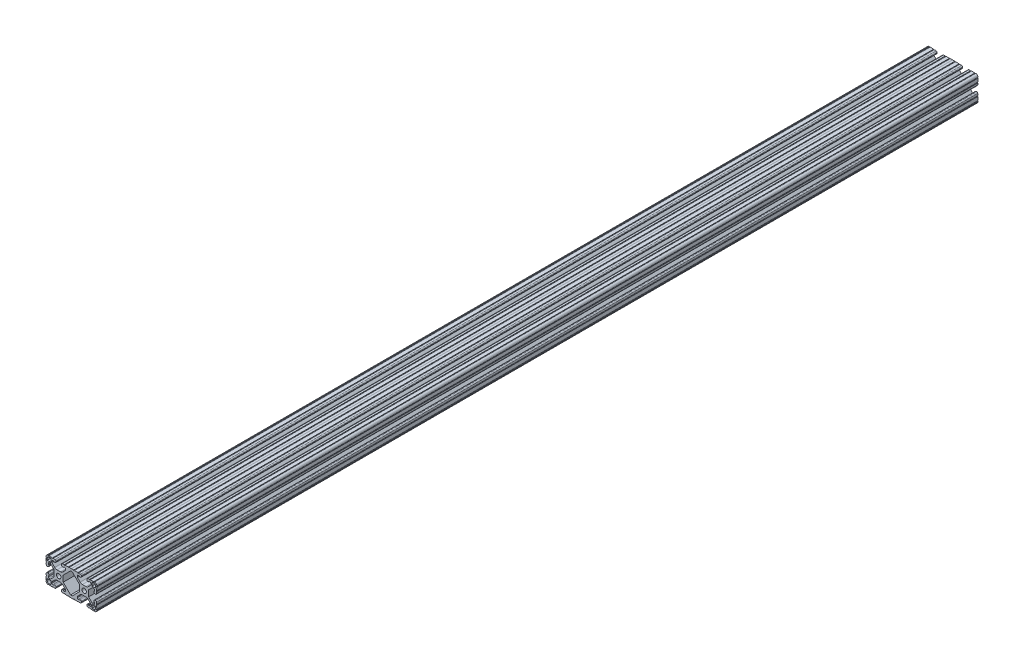
SolidWorks part; units mm, degrees
ref_plane "Front Plane" through (0, 0, 0) normal (0, 0, 1) x (1, 0, 0)
ref_plane "Top Plane" through (0, 0, 0) normal (0, 1, 0) x (1, 0, 0)
ref_plane "Right Plane" through (0, 0, 0) normal (1, 0, 0) x (0, 0, -1)
sketch "Sketch1" plane through (0, 0, 0) normal (0, 0, 1) x (1, 0, 0)
  line L0 (0, 19.05) -> (-19.1669, 19.05) construction
  line L1 (-6.7564, 0) -> (-6.7564, 4.6011)
  line L2 (-8.7357, 18.8026) -> (-15.7642, 19.0481) construction
  line L3 (-17.655, 18.5041) -> (-4.0303, 18.0283) construction
  line L4 (-5.5829, 18.6925) -> (-5.7212, 14.7325) construction
  line L5 (-11.8364, 17.2212) -> (-11.8364, 11.8364)
  line L6 (-2.6337, 6.7564) -> (0, 6.7564)
  line L7 (0, 0) -> (0, 19.05) construction
  line L8 (0, 0) -> (-19.1669, 0) construction
  line L9 (1.0776, 1.0776) -> (-1.0776, -1.0776) construction
  line L10 (-5.9923, 8.1476) -> (-9.915, 12.0703)
  line L11 (-6.7564, 4.6011) -> (-12.4423, 10.287)
  line L12 (-11.8364, 11.8364) -> (-17.2212, 11.8364)
  line L13 (0, 0) -> (-19.1669, 19.1669) construction
  line L14 (-15.7642, 19.0481) -> (-5.5829, 18.6925)
  line L15 (-4.064, 17.0637) -> (-4.0924, 16.2514)
  line L17 (-19.0481, 15.7642) -> (-18.6925, 5.5829)
  line L19 (-17.2212, 11.8364) -> (-17.2212, 14.4272)
  line L20 (-11.8364, 17.2212) -> (-14.4272, 17.2212)
  line L21 (-10.287, 12.9683) -> (-10.287, 14.3745)
  line L22 (-14.3745, 10.287) -> (-12.4423, 10.287)
  line L23 (-9.017, 15.6445) -> (-6.8707, 15.6445)
  line L24 (-6.8707, 15.6445) -> (-6.8707, 14.7325)
  line L25 (-5.7212, 14.7325) -> (-6.8707, 14.7325)
  line L26 (-17.0637, 4.064) -> (-16.2514, 4.0924)
  line L27 (-14.7325, 5.7212) -> (-14.7325, 6.8707)
  line L28 (-15.6445, 6.8707) -> (-14.7325, 6.8707)
  line L29 (-15.6445, 9.017) -> (-15.6445, 6.8707)
  circle A0 centre (0, 0) radius 3.3274
  arc A5 (-15.7642, 19.0481) -> (-19.0481, 15.7642) centre (-15.875, 15.875) ccw
  arc A7 (-9.3449, 18.8239) -> (-8.1264, 18.7813) centre (-8.7357, 18.8026) ccw
  arc A10 (-17.2212, 14.4272) -> (-14.4272, 17.2212) centre (-14.4272, 14.4272) cw
  arc A11 (-4.0924, 16.2514) -> (-5.7212, 14.7325) centre (-5.6662, 16.3064) cw
  arc A12 (-5.5829, 18.6925) -> (-4.064, 17.0637) centre (-5.6378, 17.1187) cw
  arc A13 (-5.9923, 8.1476) -> (-2.6337, 6.7564) centre (-2.6337, 11.5062) ccw
  arc A14 (-9.915, 12.0703) -> (-10.287, 12.9683) centre (-9.017, 12.9683) cw
  arc A15 (-10.287, 14.3745) -> (-9.017, 15.6445) centre (-9.017, 14.3745) cw
  arc A16 (-15.6949, 19.0456) -> (-14.4764, 19.0031) centre (-15.0857, 19.0244) ccw
  arc A17 (-18.6925, 5.5829) -> (-17.0637, 4.064) centre (-17.1187, 5.6378) ccw
  arc A18 (-16.2514, 4.0924) -> (-14.7325, 5.7212) centre (-16.3064, 5.6662) ccw
  arc A19 (-14.3745, 10.287) -> (-15.6445, 9.017) centre (-14.3745, 9.017) ccw
  arc A20 (-18.8239, 9.3449) -> (-18.7813, 8.1264) centre (-18.8026, 8.7357) cw
  arc A21 (-19.0456, 15.6949) -> (-19.0031, 14.4764) centre (-19.0244, 15.0857) cw
  point P27 (-5.7298, 13.1063)
  point P49 (-4.009, 18.6376)
  point P55 (-10.287, 12.4423)
  dimension "D1" = 6.6548
  dimension "D5" = 20.574
  dimension "D9" = 2
  dimension "D2" = 38.1
  dimension "D12" = 0.6096
  dimension "D10" = 3.175
  dimension "D13" = 2.794
  dimension "D14" = 7.2136
  dimension "D7" = 1.5748
  dimension "D20" = 4.7498
  dimension "D21" = 1.27
  dimension "D3" = 13.5128
  dimension "D4" = 13.5128
  dimension "D6" = 38.1
  dimension "D8" = 3.048
  dimension "D11" = 19.05
  dimension "D15" = 5.3848
  dimension "D16" = 3.9624
  dimension "D17" = 3.048
  dimension "D18" = 8.128
  dimension "D19" = 13.7414
  dimension "D22" = 10.3124
  dimension "D23" = 3.9624
sketch "Sketch3" plane through (0, 0, 0) normal (0, 0, 1) x (1, 0, 0)
  line L0 (0, 0) -> (19.05, 0) construction
  line L1 (19.05, 19.1628) -> (19.05, 15.6445) construction
  line L2 (15.7642, 19.0481) -> (19.05, 19.1628)
  line L3 (17.7998, 15.6445) -> (20.3002, 15.6445)
  line L4 (17.7998, -15.6445) -> (20.3002, -15.6445)
  line L5 (19.05, -15.6445) -> (19.05, -19.1628) construction
  line L6 (15.7642, -19.0481) -> (19.05, -19.1628)
  line L7 (40.7337, -6.7564) -> (35.4663, -6.7564)
  line L8 (-2.6337, 6.7564) -> (0, 6.7564) construction
  line L9 (-5.9923, 8.1476) -> (-9.915, 12.0703) construction
  line L10 (-10.287, 12.9683) -> (-10.287, 14.3745) construction
  line L11 (-9.017, 15.6445) -> (-6.8707, 15.6445) construction
  line L12 (-6.8707, 15.6445) -> (-6.8707, 14.7325) construction
  line L13 (-5.7212, 14.7325) -> (-6.8707, 14.7325) construction
  line L14 (-4.064, 17.0637) -> (-4.0924, 16.2514) construction
  line L15 (-15.7642, 19.0481) -> (-5.5829, 18.6925) construction
  line L16 (-19.0481, 15.7642) -> (-18.6925, 5.5829) construction
  line L17 (-17.0637, 4.064) -> (-16.2514, 4.0924) construction
  line L18 (-14.7325, 5.7212) -> (-14.7325, 6.8707) construction
  line L19 (-15.6445, 6.8707) -> (-14.7325, 6.8707) construction
  line L20 (-15.6445, 9.017) -> (-15.6445, 6.8707) construction
  line L21 (-14.3745, 10.287) -> (-12.4423, 10.287) construction
  line L22 (-6.7564, 4.6011) -> (-12.4423, 10.287) construction
  line L23 (-6.7564, 0) -> (-6.7564, 4.6011) construction
  line L24 (-2.6337, 6.7564) -> (2.6337, 6.7564)
  line L25 (-5.9923, 8.1476) -> (-9.915, 12.0703)
  line L26 (-10.287, 12.9683) -> (-10.287, 14.3745)
  line L27 (-9.017, 15.6445) -> (-6.8707, 15.6445)
  line L28 (-6.8707, 15.6445) -> (-6.8707, 14.7325)
  line L29 (-5.7212, 14.7325) -> (-6.8707, 14.7325)
  line L30 (-4.064, 17.0637) -> (-4.0924, 16.2514)
  line L31 (-15.7642, 19.0481) -> (-15.6949, 19.0456)
  line L32 (-19.0481, 15.7642) -> (-19.0456, 15.6949)
  line L33 (-17.0637, 4.064) -> (-16.2514, 4.0924)
  line L34 (-14.7325, 5.7212) -> (-14.7325, 6.8707)
  line L35 (-15.6445, 6.8707) -> (-14.7325, 6.8707)
  line L36 (-15.6445, 9.017) -> (-15.6445, 6.8707)
  line L37 (-14.3745, 10.287) -> (-12.4423, 10.287)
  line L38 (-6.7564, 4.6011) -> (-12.4423, 10.287)
  line L39 (-6.7564, -4.6011) -> (-6.7564, 4.6011)
  line L40 (0, 0) -> (-6.7564, 0) construction
  line L41 (0, 0) -> (0, 6.7564) construction
  line L42 (-8.1264, 18.7813) -> (-5.5829, 18.6925)
  line L43 (-14.4764, 19.0031) -> (-9.3449, 18.8239)
  line L44 (-11.8364, 11.8364) -> (-11.8364, 17.2212)
  line L45 (-17.2212, 11.8364) -> (-11.8364, 11.8364)
  line L46 (-17.2212, 14.4272) -> (-17.2212, 11.8364)
  line L47 (-11.8364, 17.2212) -> (-14.4272, 17.2212)
  line L48 (-11.8364, 11.8364) -> (-11.8364, 17.2212)
  line L49 (-17.2212, 11.8364) -> (-11.8364, 11.8364)
  line L50 (-17.2212, 14.4272) -> (-17.2212, 11.8364)
  line L51 (-11.8364, 17.2212) -> (-14.4272, 17.2212)
  line L52 (-19.0031, 14.4764) -> (-18.8239, 9.3449)
  line L53 (-18.7813, 8.1264) -> (-18.6925, 5.5829)
  line L54 (44.0923, -8.1476) -> (48.015, -12.0703)
  line L55 (48.387, -12.9683) -> (48.387, -14.3745)
  line L56 (47.117, -15.6445) -> (44.9707, -15.6445)
  line L57 (44.9707, -15.6445) -> (44.9707, -14.7325)
  line L58 (43.8212, -14.7325) -> (44.9707, -14.7325)
  line L59 (42.164, -17.0637) -> (42.1924, -16.2514)
  line L60 (14.4764, 19.0031) -> (9.3449, 18.8239)
  line L61 (8.1264, 18.7813) -> (5.5829, 18.6925)
  line L62 (6.7564, -4.6011) -> (6.7564, 4.6011)
  line L63 (6.7564, 4.6011) -> (17.7998, 15.6445)
  line L64 (53.8642, -19.0481) -> (53.7949, -19.0456)
  line L65 (57.1481, -15.7642) -> (57.1456, -15.6949)
  line L66 (55.1637, -4.064) -> (54.3514, -4.0924)
  line L67 (52.8325, -5.7212) -> (52.8325, -6.8707)
  line L68 (53.7445, -6.8707) -> (52.8325, -6.8707)
  line L69 (53.7445, -9.017) -> (53.7445, -6.8707)
  line L70 (15.7642, 19.0481) -> (15.6949, 19.0456)
  line L71 (4.064, 17.0637) -> (4.0924, 16.2514)
  line L72 (5.7212, 14.7325) -> (6.8707, 14.7325)
  line L73 (6.8707, 15.6445) -> (6.8707, 14.7325)
  line L74 (9.017, 15.6445) -> (6.8707, 15.6445)
  line L75 (10.287, 12.9683) -> (10.287, 14.3745)
  line L76 (5.9923, 8.1476) -> (9.915, 12.0703)
  line L77 (5.9923, -8.1476) -> (9.915, -12.0703)
  line L78 (10.287, -12.9683) -> (10.287, -14.3745)
  line L79 (9.017, -15.6445) -> (6.8707, -15.6445)
  line L80 (6.8707, -15.6445) -> (6.8707, -14.7325)
  line L81 (5.7212, -14.7325) -> (6.8707, -14.7325)
  line L82 (4.064, -17.0637) -> (4.0924, -16.2514)
  line L83 (15.7642, -19.0481) -> (15.6949, -19.0456)
  line L84 (52.4745, -10.287) -> (50.5423, -10.287)
  line L85 (44.8564, -4.6011) -> (50.5423, -10.287)
  line L86 (46.2264, -18.7813) -> (43.6829, -18.6925)
  line L87 (52.5764, -19.0031) -> (47.4449, -18.8239)
  line L88 (49.9364, -11.8364) -> (49.9364, -17.2212)
  line L89 (55.3212, -11.8364) -> (49.9364, -11.8364)
  line L90 (6.7564, -4.6011) -> (17.7998, -15.6445)
  line L91 (8.1264, -18.7813) -> (5.5829, -18.6925)
  line L92 (14.4764, -19.0031) -> (9.3449, -18.8239)
  line L93 (55.3212, -14.4272) -> (55.3212, -11.8364)
  line L94 (49.9364, -17.2212) -> (52.5272, -17.2212)
  line L95 (57.1031, -14.4764) -> (56.9239, -9.3449)
  line L96 (56.8813, -8.1264) -> (56.7925, -5.5829)
  line L97 (23.6236, -19.0031) -> (28.7551, -18.8239)
  line L98 (29.9736, -18.7813) -> (32.5171, -18.6925)
  line L99 (-18.7813, -8.1264) -> (-18.6925, -5.5829)
  line L100 (-19.0031, -14.4764) -> (-18.8239, -9.3449)
  line L101 (-11.8364, -17.2212) -> (-14.4272, -17.2212)
  line L102 (-17.2212, -14.4272) -> (-17.2212, -11.8364)
  line L103 (-17.2212, -11.8364) -> (-11.8364, -11.8364)
  line L104 (-11.8364, -11.8364) -> (-11.8364, -17.2212)
  line L105 (-14.4764, -19.0031) -> (-9.3449, -18.8239)
  line L106 (-8.1264, -18.7813) -> (-5.5829, -18.6925)
  line L107 (-6.7564, -4.6011) -> (-12.4423, -10.287)
  line L108 (-14.3745, -10.287) -> (-12.4423, -10.287)
  line L109 (-15.6445, -9.017) -> (-15.6445, -6.8707)
  line L110 (-15.6445, -6.8707) -> (-14.7325, -6.8707)
  line L111 (-14.7325, -5.7212) -> (-14.7325, -6.8707)
  line L112 (-17.0637, -4.064) -> (-16.2514, -4.0924)
  line L113 (-19.0481, -15.7642) -> (-19.0456, -15.6949)
  line L114 (-15.7642, -19.0481) -> (-15.6949, -19.0456)
  line L115 (-4.064, -17.0637) -> (-4.0924, -16.2514)
  line L116 (-5.7212, -14.7325) -> (-6.8707, -14.7325)
  line L117 (-6.8707, -15.6445) -> (-6.8707, -14.7325)
  line L118 (-9.017, -15.6445) -> (-6.8707, -15.6445)
  line L119 (-10.287, -12.9683) -> (-10.287, -14.3745)
  line L120 (-5.9923, -8.1476) -> (-9.915, -12.0703)
  line L121 (-2.6337, -6.7564) -> (2.6337, -6.7564)
  line L122 (31.3436, -4.6011) -> (20.3002, -15.6445)
  line L123 (22.3358, -19.0481) -> (22.4051, -19.0456)
  line L124 (34.036, -17.0637) -> (34.0076, -16.2514)
  line L125 (32.3788, -14.7325) -> (31.2293, -14.7325)
  line L126 (31.2293, -15.6445) -> (31.2293, -14.7325)
  line L127 (29.083, -15.6445) -> (31.2293, -15.6445)
  line L128 (27.813, -12.9683) -> (27.813, -14.3745)
  line L129 (32.1077, -8.1476) -> (28.185, -12.0703)
  line L130 (32.1077, 8.1476) -> (28.185, 12.0703)
  line L131 (27.813, 12.9683) -> (27.813, 14.3745)
  line L132 (29.083, 15.6445) -> (31.2293, 15.6445)
  line L133 (31.2293, 15.6445) -> (31.2293, 14.7325)
  line L134 (32.3788, 14.7325) -> (31.2293, 14.7325)
  line L135 (34.036, 17.0637) -> (34.0076, 16.2514)
  line L136 (22.3358, 19.0481) -> (22.4051, 19.0456)
  line L137 (31.3436, 4.6011) -> (20.3002, 15.6445)
  line L138 (31.3436, -4.6011) -> (31.3436, 4.6011)
  line L139 (29.9736, 18.7813) -> (32.5171, 18.6925)
  line L140 (23.6236, 19.0031) -> (28.7551, 18.8239)
  line L141 (56.8813, 8.1264) -> (56.7925, 5.5829)
  line L142 (57.1031, 14.4764) -> (56.9239, 9.3449)
  line L143 (49.9364, 17.2212) -> (52.5272, 17.2212)
  line L144 (55.3212, 14.4272) -> (55.3212, 11.8364)
  line L145 (55.3212, 11.8364) -> (49.9364, 11.8364)
  line L146 (49.9364, 11.8364) -> (49.9364, 17.2212)
  line L147 (52.5764, 19.0031) -> (47.4449, 18.8239)
  line L148 (46.2264, 18.7813) -> (43.6829, 18.6925)
  line L149 (44.8564, -4.6011) -> (44.8564, 4.6011)
  line L150 (44.8564, 4.6011) -> (50.5423, 10.287)
  line L151 (52.4745, 10.287) -> (50.5423, 10.287)
  line L152 (53.7445, 9.017) -> (53.7445, 6.8707)
  line L153 (53.7445, 6.8707) -> (52.8325, 6.8707)
  line L154 (52.8325, 5.7212) -> (52.8325, 6.8707)
  line L155 (55.1637, 4.064) -> (54.3514, 4.0924)
  line L156 (57.1481, 15.7642) -> (57.1456, 15.6949)
  line L157 (53.8642, 19.0481) -> (53.7949, 19.0456)
  line L158 (42.164, 17.0637) -> (42.1924, 16.2514)
  line L159 (43.8212, 14.7325) -> (44.9707, 14.7325)
  line L160 (44.9707, 15.6445) -> (44.9707, 14.7325)
  line L161 (47.117, 15.6445) -> (44.9707, 15.6445)
  line L162 (48.387, 12.9683) -> (48.387, 14.3745)
  line L163 (44.0923, 8.1476) -> (48.015, 12.0703)
  line L164 (40.7337, 6.7564) -> (35.4663, 6.7564)
  line L165 (22.3358, -19.0481) -> (19.05, -19.1628)
  line L166 (22.3358, 19.0481) -> (19.05, 19.1628)
  arc A0 (53.7949, -19.0456) -> (52.5764, -19.0031) centre (53.1857, -19.0244) ccw
  arc A1 (44.0923, -8.1476) -> (40.7337, -6.7564) centre (40.7337, -11.5062) ccw
  arc A2 (48.387, -12.9683) -> (48.015, -12.0703) centre (47.117, -12.9683) ccw
  arc A3 (47.117, -15.6445) -> (48.387, -14.3745) centre (47.117, -14.3745) ccw
  arc A4 (43.8212, -14.7325) -> (42.1924, -16.2514) centre (43.7662, -16.3064) ccw
  arc A5 (42.164, -17.0637) -> (43.6829, -18.6925) centre (43.7378, -17.1187) ccw
  arc A6 (53.8642, -19.0481) -> (57.1481, -15.7642) centre (53.975, -15.875) ccw
  arc A7 (56.7925, -5.5829) -> (55.1637, -4.064) centre (55.2187, -5.6378) ccw
  arc A8 (54.3514, -4.0924) -> (52.8325, -5.7212) centre (54.4064, -5.6662) ccw
  arc A9 (-15.6949, 19.0456) -> (-14.4764, 19.0031) centre (-15.0857, 19.0244) ccw construction
  arc A10 (-5.9923, 8.1476) -> (-2.6337, 6.7564) centre (-2.6337, 11.5062) ccw construction
  arc A11 (-10.287, 12.9683) -> (-9.915, 12.0703) centre (-9.017, 12.9683) ccw construction
  arc A12 (-9.017, 15.6445) -> (-10.287, 14.3745) centre (-9.017, 14.3745) ccw construction
  arc A13 (-5.7212, 14.7325) -> (-4.0924, 16.2514) centre (-5.6662, 16.3064) ccw construction
  arc A14 (-4.064, 17.0637) -> (-5.5829, 18.6925) centre (-5.6378, 17.1187) ccw construction
  arc A15 (-15.7642, 19.0481) -> (-19.0481, 15.7642) centre (-15.875, 15.875) ccw construction
  arc A16 (-18.6925, 5.5829) -> (-17.0637, 4.064) centre (-17.1187, 5.6378) ccw construction
  arc A17 (-16.2514, 4.0924) -> (-14.7325, 5.7212) centre (-16.3064, 5.6662) ccw construction
  arc A18 (-14.3745, 10.287) -> (-15.6445, 9.017) centre (-14.3745, 9.017) ccw construction
  arc A19 (-9.3449, 18.8239) -> (-8.1264, 18.7813) centre (-8.7357, 18.8026) ccw construction
  arc A20 (-18.7813, 8.1264) -> (-18.8239, 9.3449) centre (-18.8026, 8.7357) ccw construction
  arc A21 (-19.0031, 14.4764) -> (-19.0456, 15.6949) centre (-19.0244, 15.0857) ccw construction
  arc A22 (-15.6949, 19.0456) -> (-14.4764, 19.0031) centre (-15.0857, 19.0244) ccw
  arc A23 (-5.9923, 8.1476) -> (-2.6337, 6.7564) centre (-2.6337, 11.5062) ccw
  arc A24 (-10.287, 12.9683) -> (-9.915, 12.0703) centre (-9.017, 12.9683) ccw
  arc A25 (-9.017, 15.6445) -> (-10.287, 14.3745) centre (-9.017, 14.3745) ccw
  arc A26 (-5.7212, 14.7325) -> (-4.0924, 16.2514) centre (-5.6662, 16.3064) ccw
  arc A27 (-4.064, 17.0637) -> (-5.5829, 18.6925) centre (-5.6378, 17.1187) ccw
  arc A28 (-15.7642, 19.0481) -> (-19.0481, 15.7642) centre (-15.875, 15.875) ccw
  arc A29 (-18.6925, 5.5829) -> (-17.0637, 4.064) centre (-17.1187, 5.6378) ccw
  arc A30 (-16.2514, 4.0924) -> (-14.7325, 5.7212) centre (-16.3064, 5.6662) ccw
  arc A31 (-14.3745, 10.287) -> (-15.6445, 9.017) centre (-14.3745, 9.017) ccw
  arc A32 (-9.3449, 18.8239) -> (-8.1264, 18.7813) centre (-8.7357, 18.8026) ccw
  arc A33 (-18.7813, 8.1264) -> (-18.8239, 9.3449) centre (-18.8026, 8.7357) ccw
  arc A34 (-19.0031, 14.4764) -> (-19.0456, 15.6949) centre (-19.0244, 15.0857) ccw
  arc A35 (52.4745, -10.287) -> (53.7445, -9.017) centre (52.4745, -9.017) ccw
  circle A36 centre (0, 0) radius 3.3274
  circle A37 centre (0, 0) radius 3.3274
  arc A38 (-14.4272, 17.2212) -> (-17.2212, 14.4272) centre (-14.4272, 14.4272) ccw
  arc A39 (-14.4272, 17.2212) -> (-17.2212, 14.4272) centre (-14.4272, 14.4272) ccw
  arc A40 (47.4449, -18.8239) -> (46.2264, -18.7813) centre (46.8357, -18.8026) ccw
  arc A41 (56.8813, -8.1264) -> (56.9239, -9.3449) centre (56.9026, -8.7357) ccw
  arc A42 (9.3449, 18.8239) -> (8.1264, 18.7813) centre (8.7357, 18.8026) cw
  arc A43 (57.1031, -14.4764) -> (57.1456, -15.6949) centre (57.1244, -15.0857) ccw
  arc A44 (52.5272, -17.2212) -> (55.3212, -14.4272) centre (52.5272, -14.4272) ccw
  arc A45 (28.7551, -18.8239) -> (29.9736, -18.7813) centre (29.3643, -18.8026) cw
  arc A46 (34.036, -17.0637) -> (32.5171, -18.6925) centre (32.4622, -17.1187) cw
  arc A47 (4.064, 17.0637) -> (5.5829, 18.6925) centre (5.6378, 17.1187) cw
  arc A48 (5.7212, 14.7325) -> (4.0924, 16.2514) centre (5.6662, 16.3064) cw
  arc A49 (9.017, 15.6445) -> (10.287, 14.3745) centre (9.017, 14.3745) cw
  arc A50 (10.287, 12.9683) -> (9.915, 12.0703) centre (9.017, 12.9683) cw
  arc A51 (5.9923, 8.1476) -> (2.6337, 6.7564) centre (2.6337, 11.5062) cw
  arc A52 (15.6949, 19.0456) -> (14.4764, 19.0031) centre (15.0857, 19.0244) cw
  arc A53 (32.3788, -14.7325) -> (34.0076, -16.2514) centre (32.4338, -16.3064) cw
  arc A54 (15.6949, -19.0456) -> (14.4764, -19.0031) centre (15.0857, -19.0244) ccw
  arc A55 (5.9923, -8.1476) -> (2.6337, -6.7564) centre (2.6337, -11.5062) ccw
  arc A56 (10.287, -12.9683) -> (9.915, -12.0703) centre (9.017, -12.9683) ccw
  arc A57 (9.017, -15.6445) -> (10.287, -14.3745) centre (9.017, -14.3745) ccw
  arc A58 (5.7212, -14.7325) -> (4.0924, -16.2514) centre (5.6662, -16.3064) ccw
  arc A59 (4.064, -17.0637) -> (5.5829, -18.6925) centre (5.6378, -17.1187) ccw
  arc A60 (29.083, -15.6445) -> (27.813, -14.3745) centre (29.083, -14.3745) cw
  arc A61 (27.813, -12.9683) -> (28.185, -12.0703) centre (29.083, -12.9683) cw
  arc A62 (32.1077, -8.1476) -> (35.4663, -6.7564) centre (35.4663, -11.5062) cw
  arc A63 (22.4051, -19.0456) -> (23.6236, -19.0031) centre (23.0143, -19.0244) cw
  arc A64 (9.3449, -18.8239) -> (8.1264, -18.7813) centre (8.7357, -18.8026) ccw
  arc A65 (22.4051, 19.0456) -> (23.6236, 19.0031) centre (23.0143, 19.0244) ccw
  arc A66 (32.1077, 8.1476) -> (35.4663, 6.7564) centre (35.4663, 11.5062) ccw
  arc A67 (-14.4272, -17.2212) -> (-17.2212, -14.4272) centre (-14.4272, -14.4272) cw
  arc A68 (27.813, 12.9683) -> (28.185, 12.0703) centre (29.083, 12.9683) ccw
  arc A69 (-19.0031, -14.4764) -> (-19.0456, -15.6949) centre (-19.0244, -15.0857) cw
  arc A70 (-18.7813, -8.1264) -> (-18.8239, -9.3449) centre (-18.8026, -8.7357) cw
  arc A71 (-9.3449, -18.8239) -> (-8.1264, -18.7813) centre (-8.7357, -18.8026) cw
  arc A72 (-14.3745, -10.287) -> (-15.6445, -9.017) centre (-14.3745, -9.017) cw
  arc A73 (-16.2514, -4.0924) -> (-14.7325, -5.7212) centre (-16.3064, -5.6662) cw
  arc A74 (-18.6925, -5.5829) -> (-17.0637, -4.064) centre (-17.1187, -5.6378) cw
  arc A75 (-15.7642, -19.0481) -> (-19.0481, -15.7642) centre (-15.875, -15.875) cw
  arc A76 (-4.064, -17.0637) -> (-5.5829, -18.6925) centre (-5.6378, -17.1187) cw
  arc A77 (-5.7212, -14.7325) -> (-4.0924, -16.2514) centre (-5.6662, -16.3064) cw
  arc A78 (-9.017, -15.6445) -> (-10.287, -14.3745) centre (-9.017, -14.3745) cw
  arc A79 (-10.287, -12.9683) -> (-9.915, -12.0703) centre (-9.017, -12.9683) cw
  arc A80 (-5.9923, -8.1476) -> (-2.6337, -6.7564) centre (-2.6337, -11.5062) cw
  arc A81 (-15.6949, -19.0456) -> (-14.4764, -19.0031) centre (-15.0857, -19.0244) cw
  arc A82 (29.083, 15.6445) -> (27.813, 14.3745) centre (29.083, 14.3745) ccw
  arc A83 (32.3788, 14.7325) -> (34.0076, 16.2514) centre (32.4338, 16.3064) ccw
  arc A84 (34.036, 17.0637) -> (32.5171, 18.6925) centre (32.4622, 17.1187) ccw
  arc A85 (28.7551, 18.8239) -> (29.9736, 18.7813) centre (29.3643, 18.8026) ccw
  arc A86 (52.5272, 17.2212) -> (55.3212, 14.4272) centre (52.5272, 14.4272) cw
  circle A87 centre (38.1, 0) radius 3.3274
  arc A88 (57.1031, 14.4764) -> (57.1456, 15.6949) centre (57.1244, 15.0857) cw
  arc A89 (56.8813, 8.1264) -> (56.9239, 9.3449) centre (56.9026, 8.7357) cw
  arc A90 (47.4449, 18.8239) -> (46.2264, 18.7813) centre (46.8357, 18.8026) cw
  arc A91 (52.4745, 10.287) -> (53.7445, 9.017) centre (52.4745, 9.017) cw
  arc A92 (54.3514, 4.0924) -> (52.8325, 5.7212) centre (54.4064, 5.6662) cw
  arc A93 (56.7925, 5.5829) -> (55.1637, 4.064) centre (55.2187, 5.6378) cw
  arc A94 (53.8642, 19.0481) -> (57.1481, 15.7642) centre (53.975, 15.875) cw
  arc A95 (42.164, 17.0637) -> (43.6829, 18.6925) centre (43.7378, 17.1187) cw
  arc A96 (43.8212, 14.7325) -> (42.1924, 16.2514) centre (43.7662, 16.3064) cw
  arc A97 (47.117, 15.6445) -> (48.387, 14.3745) centre (47.117, 14.3745) cw
  arc A98 (48.387, 12.9683) -> (48.015, 12.0703) centre (47.117, 12.9683) cw
  arc A99 (44.0923, 8.1476) -> (40.7337, 6.7564) centre (40.7337, 11.5062) cw
  arc A100 (53.7949, 19.0456) -> (52.5764, 19.0031) centre (53.1857, 19.0244) cw
  point P201 (6.7564, 0)
  point P293 (31.3436, 0)
  dimension "D2" = 3.048
  dimension "D3" = 19.05
  dimension "D1" = 0
extrude "Extrude1" add sketch "Sketch3" along normal mid plane 1828.8
sketch "Sketch4" plane through (0, 0, -914.4) normal (0, 0, -1) x (-1, 0, 0)
  line L1 (-58.7594, 19.6469) -> (20.3233, 19.6469)
  line L2 (-58.7594, 19.6469) -> (-58.7594, -20.0712)
  line L3 (-58.7594, -20.0712) -> (20.3233, -20.0712)
  line L4 (20.3233, 19.6469) -> (20.3233, -20.0712)
extrude "Cut-Extrude1" cut sketch "Sketch4" against normal blind 508
equation "\"D11@Sketch1\" = \"D6@Sketch1\"/2"
equation "\"D2@Sketch3\" = \"D8@Sketch1\"*1"
equation "\"D16@Sketch1\" = \"D8@Sketch1\"*1.3"
equation "\"D17@Sketch1\" = \"D8@Sketch1\""
equation "\"D12@Sketch1\" = \"D8@Sketch1\"/5"
